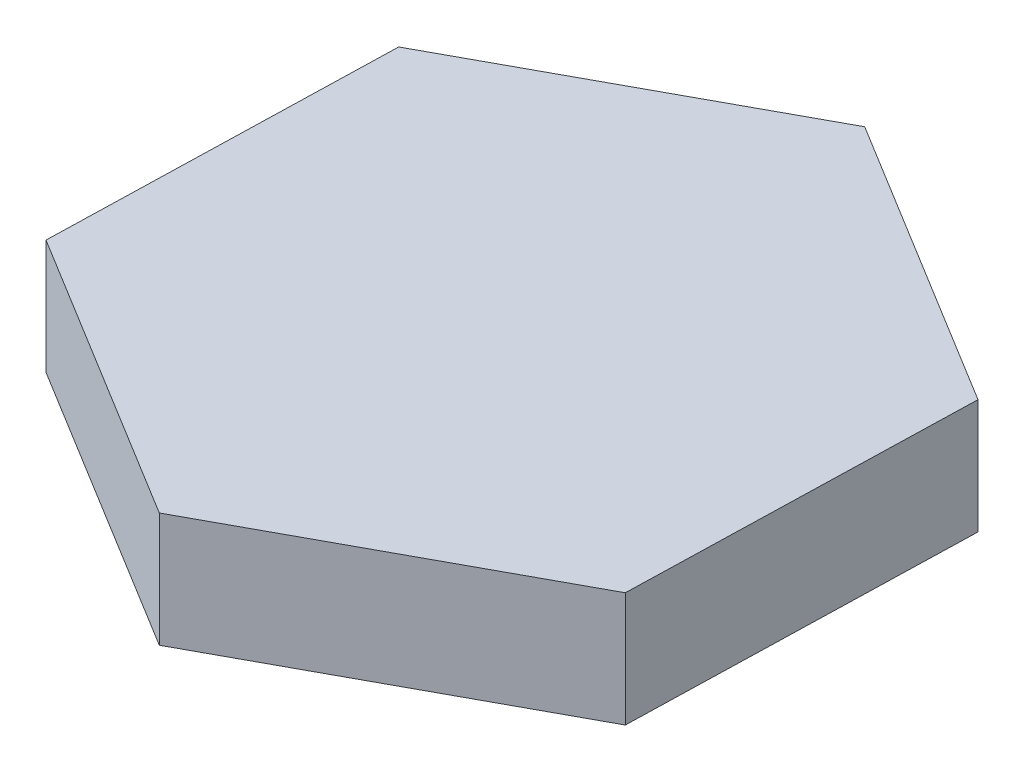
SolidWorks part; units mm, degrees
ref_plane "Alzado" through (0, 0, 0) normal (0, 0, 1) x (1, 0, 0)
ref_plane "Planta" through (0, 0, 0) normal (0, 1, 0) x (1, 0, 0)
ref_plane "Vista lateral" through (0, 0, 0) normal (1, 0, 0) x (0, 0, -1)
sketch "Croquis1" plane through (0, 0, 0) normal (0, 1, 0) x (1, 0, 0)
  line L4 (0.7956, 29.9894) -> (-25.5738, 15.6838)
  line L5 (-25.5738, 15.6838) -> (-26.3694, -14.3057)
  line L6 (-26.3694, -14.3057) -> (-0.7956, -29.9894)
  line L7 (-0.7956, -29.9894) -> (25.5738, -15.6838)
  line L8 (25.5738, -15.6838) -> (26.3694, 14.3057)
  line L9 (26.3694, 14.3057) -> (0.7956, 29.9894)
  circle A0 centre (0, 0) radius 25.9808 construction
  dimension "D1" = 30
extrude "Saliente-Extruir1" add sketch "Croquis1" along normal blind 10
